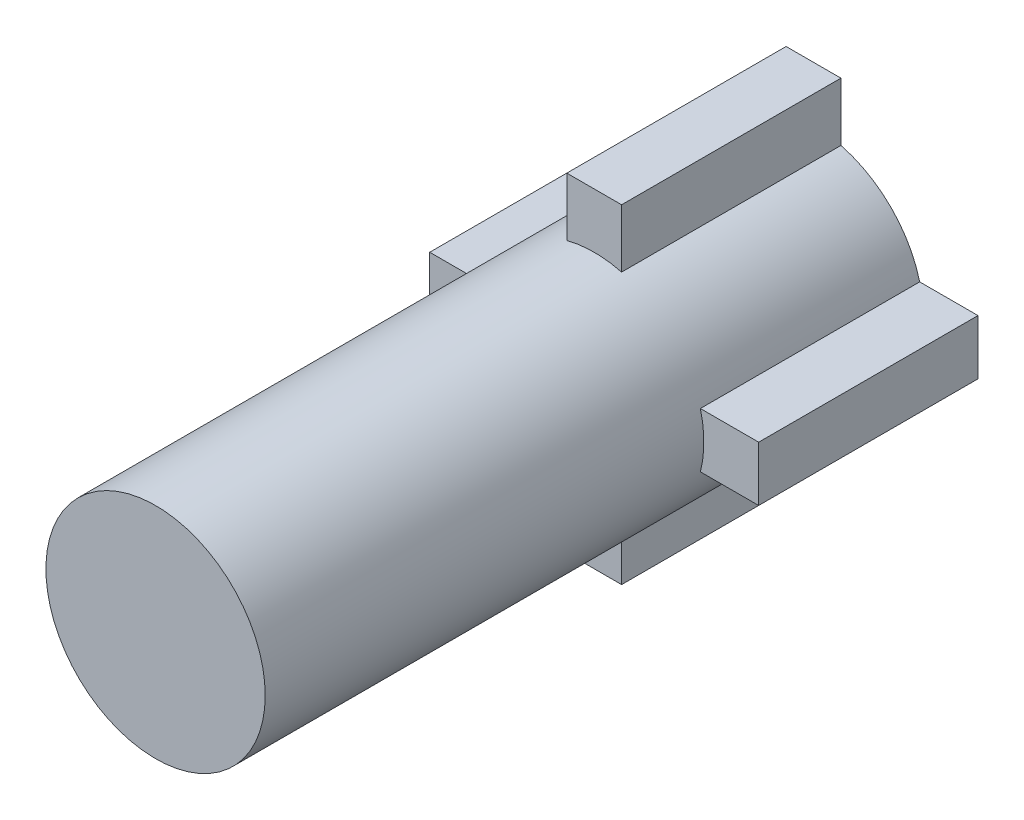
SolidWorks part; units mm, degrees
ref_plane "Front Plane" through (0, 0, 0) normal (0, 0, 1) x (1, 0, 0)
ref_plane "Top Plane" through (0, 0, 0) normal (0, 1, 0) x (1, 0, 0)
ref_plane "Right Plane" through (0, 0, 0) normal (1, 0, 0) x (0, 0, -1)
sketch "Sketch3" plane through (0, 0, 0) normal (0, 0, 1) x (1, 0, 0)
  circle A0 centre (0, 0) radius 0.1
  dimension "D1" = 0.2
extrude "Boss-Extrude1" add sketch "Sketch3" along normal mid plane 0.6
sketch "Sketch4" plane through (0, 0, -0.3) normal (0, 0, -1) x (-1, 0, 0)
  line L0 (0, -133.7304) -> (0, 133.7304) construction
  line L1 (-0.15, -0.025) -> (-0.15, 0.025)
  line L2 (-0.15, -0.025) -> (-0.05, -0.025)
  line L3 (-0.15, 0.025) -> (-0.05, 0.025)
  line L4 (-0.05, -0.025) -> (-0.05, 0.025)
  line L5 (-0.15, -0.025) -> (-0.05, 0.025) construction
  line L6 (-0.15, 0.025) -> (-0.05, -0.025) construction
  line L7 (-0.025, 0.15) -> (0.025, 0.15)
  line L8 (-0.025, 0.15) -> (-0.025, 0.05)
  line L9 (0.025, 0.15) -> (0.025, 0.05)
  line L10 (-0.025, 0.05) -> (0.025, 0.05)
  line L11 (-0.025, 0.15) -> (0.025, 0.05) construction
  line L12 (0.025, 0.15) -> (-0.025, 0.05) construction
  line L13 (0.15, 0.025) -> (0.15, -0.025)
  line L14 (0.15, 0.025) -> (0.05, 0.025)
  line L15 (0.15, -0.025) -> (0.05, -0.025)
  line L16 (0.05, 0.025) -> (0.05, -0.025)
  line L17 (0.15, 0.025) -> (0.05, -0.025) construction
  line L18 (0.15, -0.025) -> (0.05, 0.025) construction
  line L19 (0.025, -0.15) -> (-0.025, -0.15)
  line L20 (0.025, -0.15) -> (0.025, -0.05)
  line L21 (-0.025, -0.15) -> (-0.025, -0.05)
  line L22 (0.025, -0.05) -> (-0.025, -0.05)
  line L23 (0.025, -0.15) -> (-0.025, -0.05) construction
  line L24 (-0.025, -0.15) -> (0.025, -0.05) construction
  circle A0 centre (0, 0) radius 0.1 construction
  point P4 (0, 0)
  point P6 (-0.1, 0)
  point P15 (0, 0.1)
  point P20 (0.1, 0)
  point P25 (0, -0.1)
  point P30 (0, 0)
  dimension "D1" = 0.1
  dimension "D2" = 0.05
  dimension "D4" = 4
extrude "Boss-Extrude2" add sketch "Sketch4" against normal blind 0.2
